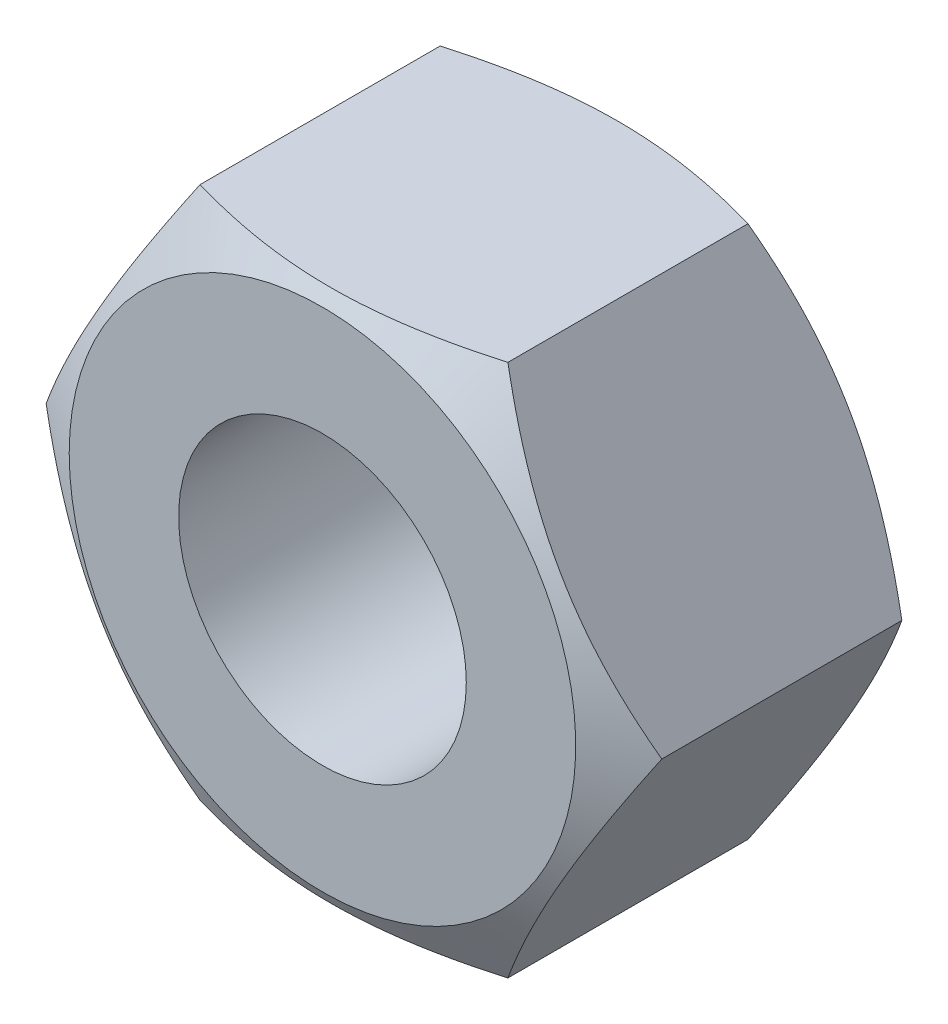
SolidWorks part; units mm, degrees
ref_plane "Plane1" through (0, 0, 0) normal (0, 0, 1) x (1, 0, 0)
ref_plane "Plane2" through (0, 0, 0) normal (0, 1, 0) x (1, 0, 0)
ref_plane "Plane3" through (0, 0, 0) normal (1, 0, 0) x (0, 0, -1)
sketch "BaseNutSke" plane through (0, 0, 0) normal (0, 0, 1) x (1, 0, 0)
  line L6 (5.4848, -9.5) -> (-5.4848, -9.5)
  line L7 (5.4848, 9.5) -> (-5.4848, 9.5)
  line L8 (5.4848, -9.5) -> (10.9697, 0)
  line L9 (10.9697, 0) -> (5.4848, 9.5)
  line L10 (-5.4848, 9.5) -> (-10.9697, 0)
  line L11 (-10.9697, 0) -> (-5.4848, -9.5)
  circle A0 centre (0, 0) radius 5.125 construction
  circle A1 centre (0, 0) radius 10.9697 construction
  circle A2 centre (0, 0) radius 5.125
  dimension "Tap_drill" = 10.25
  dimension "Diameter" = 10.25
  dimension "Width_flats" = 19
extrude "BaseNut" add sketch "BaseNutSke" against normal blind 10.8
cosmetic thread "ThreadCosmetic" parameters "Thread_major"=12
ref_plane "Plane4" through (0, 0, -5.4) normal (0, 0, -1) x (-1, 0, 0)
sketch "Sketch6" plane through (0, 0, -10.8) normal (0, 0, -1) x (-1, 0, 0)
  circle A0 centre (0, 0) radius 9.025
  dimension "D1" = 18.05
extrude "Cut-Extrude2" cut sketch "Sketch6" against normal through all draft 60 flip side to cut
mirror "Mirror1" about plane through (0, 0, -5.4) normal (0, 0, -1) of "Cut-Extrude2"
equation "\"D1@Sketch3\" = \"Width_flats@BaseNutSke\" /2"
equation "' \"Num_threads@ThdSchPat\" = \"Num_threads@ThdSchPat\" - sgn( \"Num_threads@ThdSchPat\" - 1) '---chamfered tips only---"
equation "\"D1@Sketch6\" = 0.95 * \"Width_flats@BaseNutSke\""
